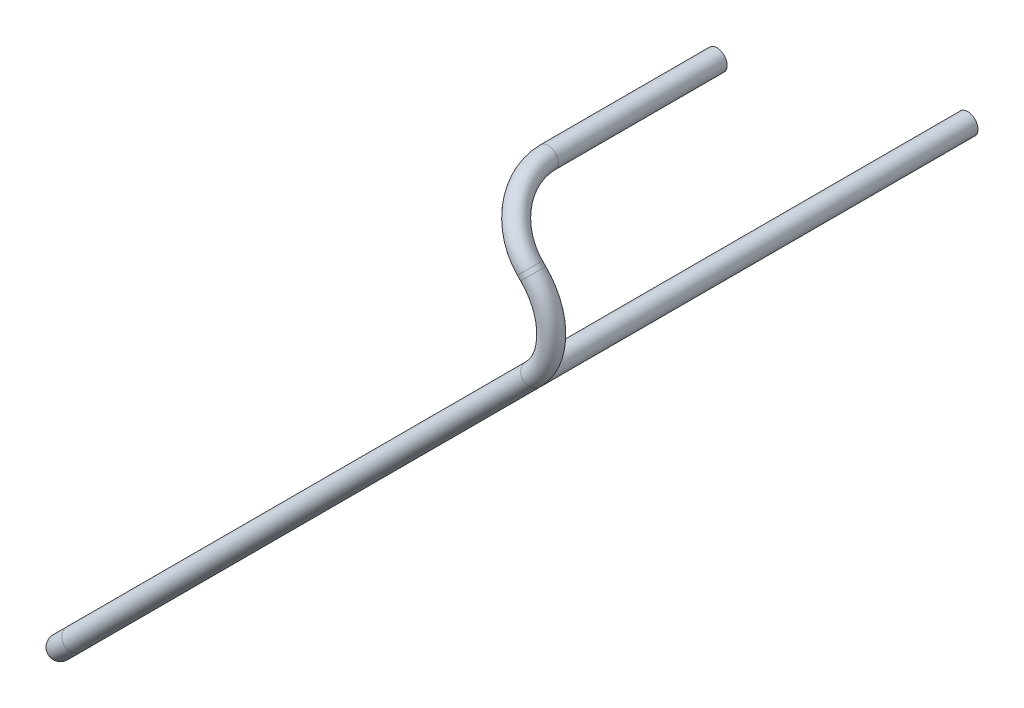
SolidWorks part; units mm, degrees
ref_plane "Front" through (0, 0, 0) normal (0, 0, 1) x (1, 0, 0)
ref_plane "Top" through (0, 0, 0) normal (0, 1, 0) x (1, 0, 0)
ref_plane "Side" through (0, 0, 0) normal (1, 0, 0) x (0, 0, -1)
sketch "PipeSketch" plane through (0, 0, 0) normal (0, 0, 1) x (1, 0, 0)
  circle A0 centre (0, 0) radius 6.35
  circle A1 centre (0, 0) radius 5.1054 construction
  dimension "OuterDiameter" = 12.7
  dimension "InnerDiameter" = 10.2108
sketch "FilterSketch" plane through (0, 0, 0) normal (0, 0, 1) x (1, 0, 0)
  circle A0 centre (0, 0) radius 6.35 construction
  dimension "NominalDiameter" = 12.7
sketch3d "3DSketch1"
  line L0 (0, 0, 0) -> (0, 0, 541.7796) construction
  line L1 (26.9408, 26.9408, 579.8796) -> (310.9775, 310.9775, 579.8796) construction
  line L2 (310.9775, 364.859, 579.8796) -> (308.9516, 366.8848, 579.8796) construction
  line L3 (282.0109, 393.8256, 437.2281) -> (282.0109, 393.8256, 541.7796) construction
  line L4 (0, 0, 0) -> (0, 0, 541.7796)
  line L5 (26.9408, 26.9408, 579.8796) -> (310.9775, 310.9775, 579.8796)
  line L6 (310.9775, 364.859, 579.8796) -> (308.9516, 366.8848, 579.8796)
  line L7 (282.0109, 393.8256, 437.2281) -> (282.0109, 393.8256, 541.7796)
  arc A0 (0, 0, 541.7796) -> (26.9408, 26.9408, 579.8796) centre (26.9408, 26.9408, 541.7796) ccw construction
  arc A1 (310.9775, 310.9775, 579.8796) -> (310.9775, 364.859, 579.8796) centre (284.0367, 337.9182, 579.8796) ccw construction
  arc A2 (308.9516, 366.8848, 579.8796) -> (282.0109, 393.8256, 541.7796) centre (308.9516, 366.8848, 541.7796) ccw construction
  arc A3 (0, 0, 541.7796) -> (26.9408, 26.9408, 579.8796) centre (26.9408, 26.9408, 541.7796) ccw
  arc A4 (310.9775, 310.9775, 579.8796) -> (310.9775, 364.859, 579.8796) centre (284.0367, 337.9182, 579.8796) ccw
  arc A5 (308.9516, 366.8848, 579.8796) -> (282.0109, 393.8256, 541.7796) centre (308.9516, 366.8848, 541.7796) ccw
  point P4 (0, 53.8815, 541.7796)
  point P6 (0, 53.8815, 541.7796)
  point P7 (284.0367, 337.9182, 617.9796)
  point P10 (282.0109, 339.9441, 541.7796)
  point P12 (284.0367, 337.9182, 617.9796)
  point P18 (282.0109, 339.9441, 541.7796)
sweep "ThinSweep" add profiles "PipeSketch" path "3DSketch1" parameters "WallThickness"=1.2446
ref_plane "Plane1" through (0, 0, 0) normal (0, 0, 1) x (1, 0, 0)
